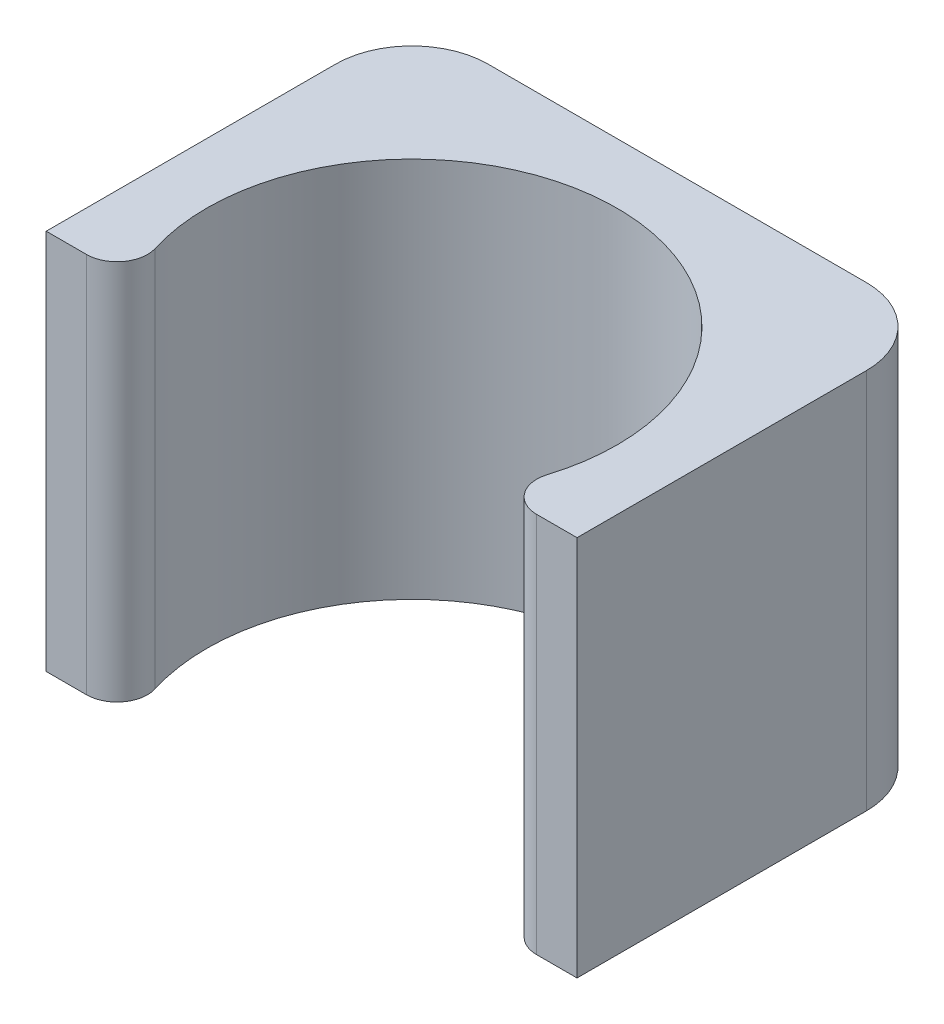
SolidWorks part; units mm, degrees
ref_plane "Front Plane" through (0, 0, 0) normal (0, 0, 1) x (1, 0, 0)
ref_plane "Top Plane" through (0, 0, 0) normal (0, 1, 0) x (1, 0, 0)
ref_plane "Right Plane" through (0, 0, 0) normal (1, 0, 0) x (0, 0, -1)
sketch "Sketch1" plane through (0, 0, 0) normal (0, 1, 0) x (1, 0, 0)
  line L1 (-34.8, 0) -> (-34.8, -23.97)
  line L2 (-34.8, -23.97) -> (-32.1586, -23.97)
  line L3 (-2.6414, -23.97) -> (0, -23.97)
  line L4 (0, -23.97) -> (0, 0)
  line L7 (-34.8, 0) -> (0, 0)
  arc A0 (-30.2481, -21.3784) -> (-4.5519, -21.3784) centre (-17.4, -17.4) cw
  arc A1 (-4.5519, -21.3784) -> (-2.6414, -23.97) centre (-2.6414, -21.97) ccw
  arc A2 (-32.1586, -23.97) -> (-30.2481, -21.3784) centre (-32.1586, -21.97) ccw
  dimension "D2" = 13.45
  dimension "D5" = 2
  dimension "D1" = 23.97
  dimension "D3" = 17.4
  dimension "D4" = 34.8
extrude "Boss-Extrude1" add sketch "Sketch1" along normal blind 25
fillet "Fillet1" radius 5 2 edges at (0, 12.5, 0) (-34.8, 12.5, 0)
